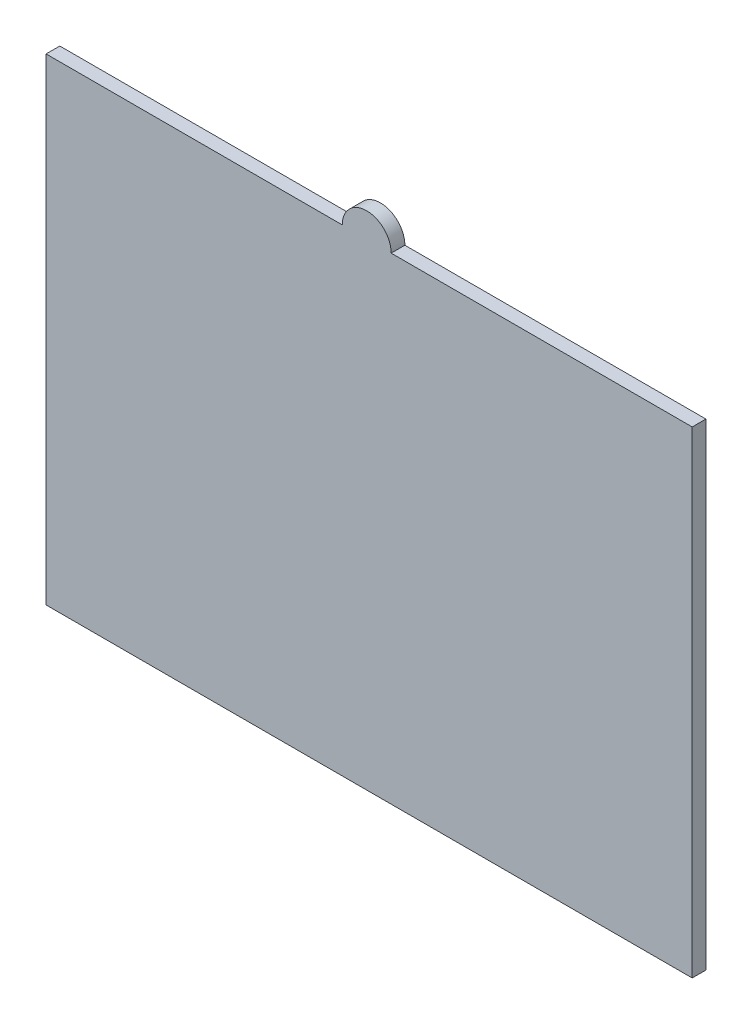
SolidWorks part; units mm, degrees
ref_plane "Front Plane" through (0, 0, 0) normal (0, 0, 1) x (1, 0, 0)
ref_plane "Top Plane" through (0, 0, 0) normal (0, 1, 0) x (1, 0, 0)
ref_plane "Right Plane" through (0, 0, 0) normal (1, 0, 0) x (0, 0, -1)
sketch "Sketch1" plane through (0, 0, 0) normal (0, 0, 1) x (1, 0, 0)
  line L0 (5, 48.5) -> (66.5, 48.5)
  line L1 (-65.5, 48.5) -> (-5, 48.5)
  line L2 (-65.5, 48.5) -> (-65.5, -49)
  line L3 (-65.5, -49) -> (66.5, -49)
  line L4 (66.5, 48.5) -> (66.5, -49)
  arc A0 (5, 48.5) -> (-5, 48.5) centre (0, 48.5) ccw
  point P0 (0, 0)
  dimension "D3" = 10
  dimension "D1" = 97.5
  dimension "D2" = 132
extrude "Boss-Extrude1" add sketch "Sketch1" along normal blind 2.8
